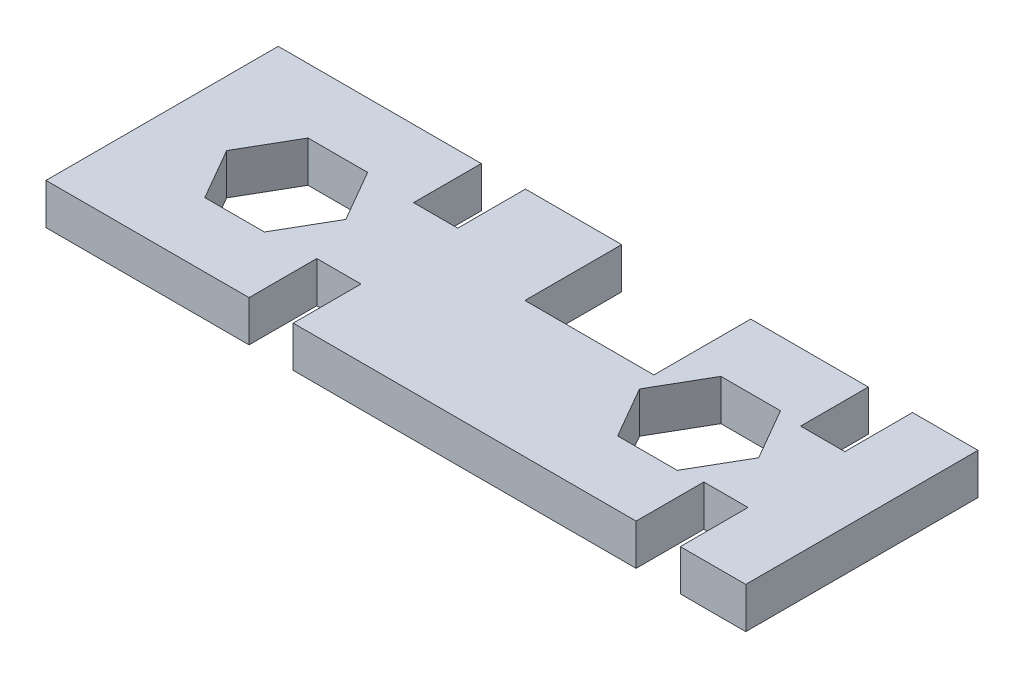
SolidWorks part; units mm, degrees
ref_plane "Front Plane" through (0, 0, 0) normal (0, 0, 1) x (1, 0, 0)
ref_plane "Top Plane" through (0, 0, 0) normal (0, 1, 0) x (1, 0, 0)
ref_plane "Right Plane" through (0, 0, 0) normal (1, 0, 0) x (0, 0, -1)
other "Default"
sketch "Sketch1" plane through (0, 0, 0) normal (0, 1, 0) x (1, 0, 0)
  line L0 (-32, 0) -> (32, 0) construction
  line L1 (-22.7624, 0) -> (-27.3812, 8)
  line L2 (-27.3812, 8) -> (-36.6188, 8)
  line L3 (-36.6188, 8) -> (-41.2376, 0)
  line L4 (-41.2376, 0) -> (-36.6188, -8)
  line L5 (-36.6188, -8) -> (-27.3812, -8)
  line L6 (-27.3812, -8) -> (-22.7624, 0)
  line L7 (41.2376, 0) -> (36.6188, 8)
  line L8 (36.6188, 8) -> (27.3812, 8)
  line L9 (27.3812, 8) -> (22.7624, 0)
  line L10 (22.7624, 0) -> (27.3812, -8)
  line L11 (27.3812, -8) -> (36.6188, -8)
  line L12 (36.6188, -8) -> (41.2376, 0)
  line L14 (-51.2376, 18) -> (57.2376, 18)
  line L15 (-51.2376, 18) -> (-51.2376, -72.5)
  line L16 (-51.2376, -72.5) -> (57.2376, -72.5)
  line L17 (57.2376, 18) -> (57.2376, -72.5)
  circle A0 centre (-32, 0) radius 8 construction
  circle A1 centre (32, 0) radius 8 construction
  dimension "D1" = 16
  dimension "D2" = 64
  dimension "D3" = 10
  dimension "D4" = 10
  dimension "D5" = 90.5
  dimension "D6" = 16
extrude "Boss-Extrude1" add sketch "Sketch1" along normal mid plane 6.35
sketch "Sketch2" plane through (0, 3.175, 0) normal (0, 1, 0) x (1, 0, 0)
  line L0 (57.2376, 18) -> (-51.2376, 18) construction
  line L1 (-19.7624, 18) -> (-12.9124, 18)
  line L2 (-19.7624, 18) -> (-19.7624, 7.5)
  line L3 (-19.7624, 7.5) -> (-12.9124, 7.5)
  line L4 (-12.9124, 18) -> (-12.9124, 7.5)
  line L5 (-51.2376, -72.5) -> (57.2376, -72.5) construction
  line L6 (-19.7624, -72.5) -> (-12.9124, -72.5)
  line L7 (-19.7624, -72.5) -> (-19.7624, -62)
  line L8 (-19.7624, -62) -> (-12.9124, -62)
  line L9 (-12.9124, -72.5) -> (-12.9124, -62)
  line L10 (-16.3374, -22) -> (-16.3374, 7.5) construction
  line L11 (-19.7624, -32.5) -> (-12.9124, -32.5)
  line L12 (-19.7624, -32.5) -> (-19.7624, -22)
  line L13 (-19.7624, -22) -> (-12.9124, -22)
  line L14 (-12.9124, -32.5) -> (-12.9124, -22)
  line L15 (-16.3374, -62) -> (-16.3374, -32.5) construction
  dimension "D1" = 6.85
  dimension "D2" = 10.5
  dimension "D3" = 3
extrude "Cut-Extrude1" cut sketch "Sketch2" against normal through all
pattern_linear "LPattern1" count 2 spacing 60 along (1, 0, 0) of "Cut-Extrude1"
sketch "Sketch3" plane through (0, 3.175, 0) normal (0, 1, 0) x (1, 0, 0)
  line L0 (40.2376, 18) -> (-12.9124, 18) construction
  line L1 (2.0024, 18) -> (21.9976, 18)
  line L2 (2.0024, 18) -> (2.0024, 3)
  line L3 (2.0024, 3) -> (21.9976, 3)
  line L4 (21.9976, 18) -> (21.9976, 3)
  line L5 (57.2376, -72.5) -> (57.2376, 18) construction
  line L6 (-51.2376, 18) -> (-51.2376, -72.5) construction
  dimension "D1" = 35.24
  dimension "D2" = 53.24
  dimension "D3" = 15
extrude "Cut-Extrude2" cut sketch "Sketch3" against normal through all
sketch "Sketch4" plane through (0, 3.175, 0) normal (0, 1, 0) x (1, 0, 0)
  line L0 (47.0876, -72.5) -> (47.0876, -62) construction
  line L1 (47.0876, -69.5) -> (53.9376, -69.5)
  line L2 (47.0876, -69.5) -> (47.0876, -59)
  line L3 (47.0876, -59) -> (53.9376, -59)
  line L4 (53.9376, -69.5) -> (53.9376, -59)
  line L5 (47.0876, -37.2) -> (53.9376, -37.2)
  line L6 (47.0876, -37.2) -> (47.0876, -26.7)
  line L7 (47.0876, -26.7) -> (53.9376, -26.7)
  line L8 (53.9376, -37.2) -> (53.9376, -26.7)
  line L9 (47.0876, -72.5) -> (57.2376, -72.5) construction
  point P9 (47.0876, -64.25)
  point P10 (47.0876, -31.95)
  dimension "D1" = 32.3
  dimension "D2" = 10.5
  dimension "D3" = 6.85
  dimension "D4" = 3
extrude "Cut-Extrude3" cut sketch "Sketch4" against normal through all
sketch "Sketch5" plane through (0, 3.175, 0) normal (0, 1, 0) x (1, 0, 0)
  line L0 (57.2376, -72.5) -> (57.2376, 18) construction
  line L1 (-51.2376, -72.5) -> (57.2376, -72.5)
  line L2 (-51.2376, -72.5) -> (-51.2376, -18)
  line L4 (57.2376, -72.5) -> (57.2376, -18)
  line L6 (-19.7624, 18) -> (-19.7624, 7.5) construction
  line L8 (-19.7624, -18) -> (-19.7624, -7.5)
  line L9 (-19.7624, -7.5) -> (-12.9124, -7.5)
  line L10 (-12.9124, -18) -> (-12.9124, -7.5)
  line L12 (40.2376, -18) -> (40.2376, -7.5)
  line L13 (40.2376, -7.5) -> (47.0876, -7.5)
  line L14 (47.0876, -18) -> (47.0876, -7.5)
  line L15 (-12.9124, 7.5) -> (-12.9124, 18) construction
  line L16 (40.2376, 18) -> (40.2376, 7.5) construction
  line L17 (47.0876, 7.5) -> (47.0876, 18) construction
  line L18 (-51.2376, -18) -> (-19.7624, -18)
  line L19 (-12.9124, -18) -> (40.2376, -18)
  line L20 (47.0876, -18) -> (57.2376, -18)
  line L21 (-36.6188, -8) -> (-27.3812, -8) construction
  dimension "D1" = 10
extrude "Short" cut sketch "Sketch5" against normal through all
